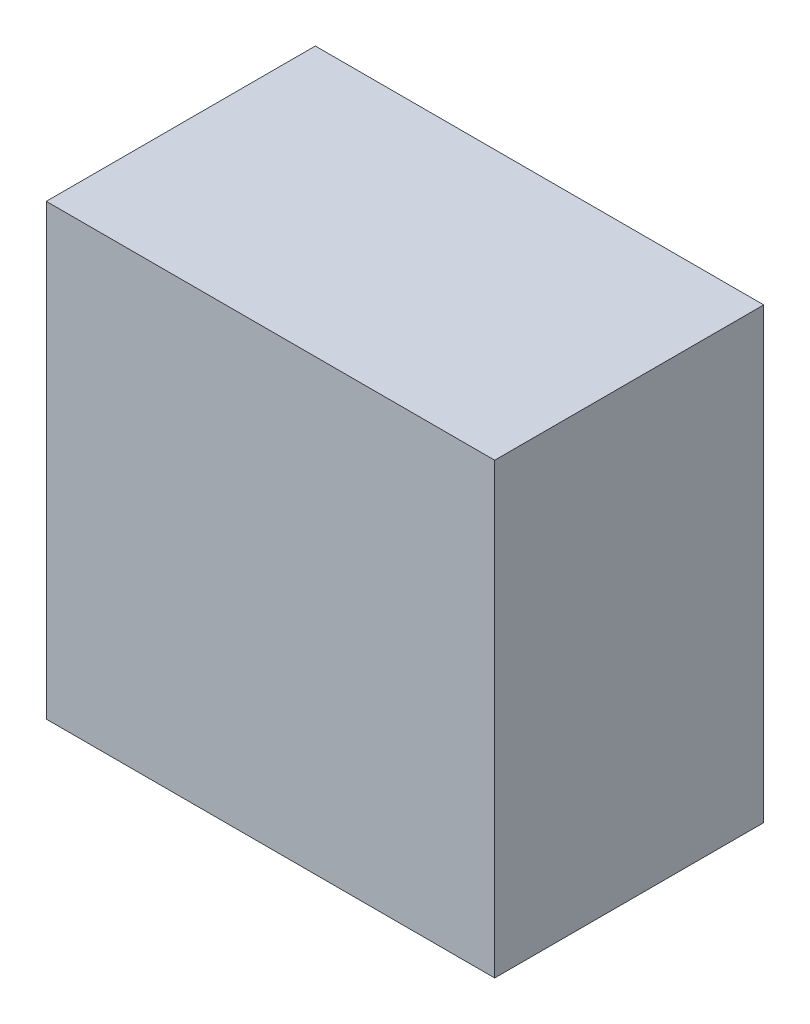
SolidWorks part; units mm, degrees
material "Custom Plastic"
ref_plane "Front Plane" through (0, 0, 0) normal (0, 0, 1) x (1, 0, 0)
ref_plane "Top Plane" through (0, 0, 0) normal (0, 1, 0) x (1, 0, 0)
ref_plane "Right Plane" through (0, 0, 0) normal (1, 0, 0) x (0, 0, -1)
sketch "Sketch1" plane through (0, 0, 0) normal (0, 0, 1) x (1, 0, 0)
  line L1 (-75, -75) -> (75, -75)
  line L2 (-75, -75) -> (-75, 75)
  line L3 (-75, 75) -> (75, 75)
  line L4 (75, -75) -> (75, 75)
  line L5 (-75, -75) -> (75, 75) construction
  line L6 (-75, 75) -> (75, -75) construction
  point P0 (0, 0)
extrude "Boss-Extrude1" add sketch "Sketch1" along normal blind 90
